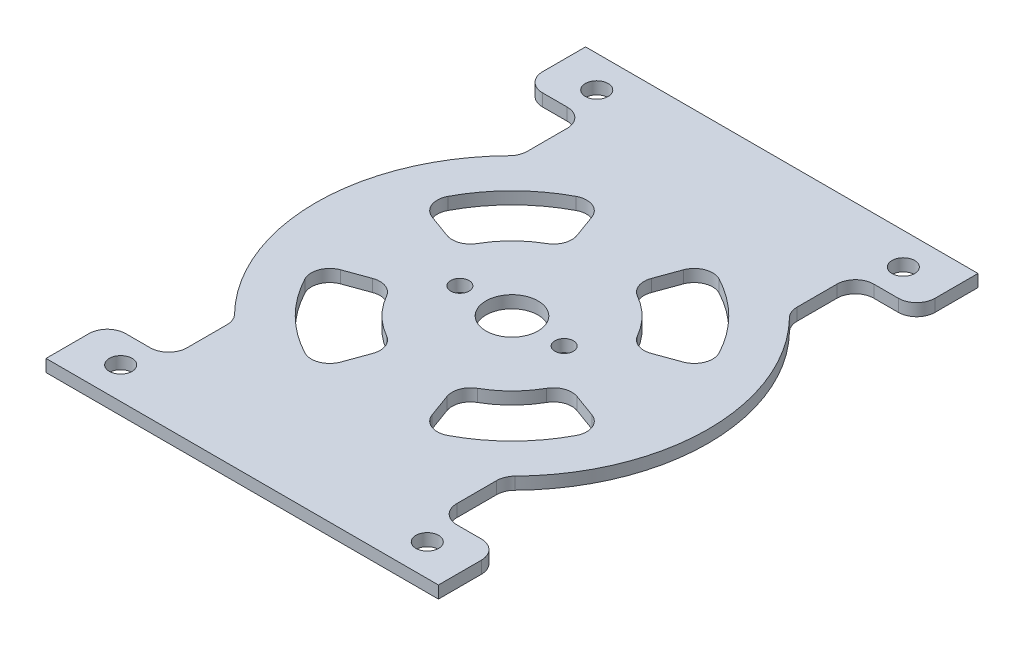
SolidWorks part; units mm, degrees
material "Acrylic (Medium-high impact)"
ref_plane "Front Plane" through (0, 0, 0) normal (0, 0, 1) x (1, 0, 0)
ref_plane "Top Plane" through (0, 0, 0) normal (0, 1, 0) x (1, 0, 0)
ref_plane "Right Plane" through (0, 0, 0) normal (1, 0, 0) x (0, 0, -1)
sketch "Sketch1" plane through (0, 0, 0) normal (0, 1, 0) x (1, 0, 0)
  line L0 (-32, 44) -> (-32, 37)
  line L1 (32, -44) -> (-32, -44)
  line L3 (32, 44) -> (-32, 44)
  line L5 (32, -44) -> (-32, 44) construction
  line L6 (32, 44) -> (-32, -44) construction
  line L7 (-29, 34) -> (-25, 34)
  line L8 (-22, 31) -> (-22, 24.4949)
  line L9 (-32, 34) -> (-32, 44)
  line L10 (32, 44) -> (32, 37)
  line L11 (29, 34) -> (25, 34)
  line L12 (22, 31) -> (22, 24.4949)
  line L13 (-55, 0) -> (55, 0) construction
  line L14 (-22, -31) -> (-22, -24.4949)
  line L15 (-29, -34) -> (-25, -34)
  line L16 (-32, -44) -> (-32, -37)
  line L17 (32, -44) -> (32, -37)
  line L18 (22, -31) -> (22, -24.4949)
  line L19 (29, -34) -> (25, -34)
  circle A0 centre (0, 0) radius 4.25
  arc A1 (-22.8571, 22.3953) -> (-22.8571, -22.3953) centre (0, 0) ccw
  arc A3 (22.8571, -22.3953) -> (22.8571, 22.3953) centre (0, 0) ccw
  arc A4 (-22, 24.4949) -> (-22.8571, 22.3953) centre (-25, 24.4949) cw
  arc A5 (-32, 37) -> (-29, 34) centre (-29, 37) ccw
  arc A6 (-25, 34) -> (-22, 31) centre (-25, 31) cw
  arc A7 (32, 37) -> (29, 34) centre (29, 37) cw
  arc A8 (25, 34) -> (22, 31) centre (25, 31) ccw
  arc A9 (22, 24.4949) -> (22.8571, 22.3953) centre (25, 24.4949) ccw
  arc A10 (32, -37) -> (29, -34) centre (29, -37) ccw
  arc A11 (22, -31) -> (25, -34) centre (25, -31) ccw
  arc A12 (22, -24.4949) -> (22.8571, -22.3953) centre (25, -24.4949) cw
  arc A13 (-22, -24.4949) -> (-22.8571, -22.3953) centre (-25, -24.4949) ccw
  arc A14 (-22, -31) -> (-25, -34) centre (-25, -31) cw
  arc A15 (-29, -34) -> (-32, -37) centre (-29, -37) ccw
  point P0 (0, 0)
  point P25 (-22, 23.2379)
  point P31 (-22, 34)
  point P34 (32, 34)
  point P37 (22, 34)
  point P40 (22, 23.2379)
  point P43 (32, -34)
  point P46 (22, -34)
  point P49 (22, -23.2379)
  point P52 (-22, -23.2379)
  point P55 (-22, -34)
  point P58 (-32, -34)
  dimension "D3" = 8.5
  dimension "D5" = 64
  dimension "D10" = 3
  dimension "D1" = 64
  dimension "D2" = 88
  dimension "D6" = 10
  dimension "D7" = 10
  dimension "D8" = 10
  dimension "D9" = 10
extrude "Boss-Extrude1" add sketch "Sketch1" along normal blind 2 contours L15 A15 L16 L1 L17 A10 L19 A11 L18 A12 A3 A9 L12 A8 L11 A7 L10 L3 L0 A5 L7 A6 L8 A4 A1 A13 L14 A14 A0
sketch "Sketch2" plane through (0, 2, 0) normal (0, 1, 0) x (1, 0, 0)
  line L0 (0, 34.8617) -> (0, -39.3717) construction
  line L1 (-36.4463, 0) -> (53.8771, 0) construction
  line L2 (42.9011, -15.6147) -> (0, 0)
  line L3 (10.8296, -29.754) -> (0, 0)
  line L4 (-6.0703, 16.6779) -> (-7.4542, 20.4801)
  line L5 (-16.6779, 6.0703) -> (-20.4801, 7.4542)
  arc A0 (-11.6741, 22.1069) -> (-22.1069, 11.6741) centre (0, 0) ccw
  arc A1 (-7.4078, 13.0432) -> (-13.0432, 7.4078) centre (0, 0) ccw
  arc A2 (-22.1069, 11.6741) -> (-20.4801, 7.4542) centre (-19.4541, 10.2732) ccw
  arc A3 (-13.0432, 7.4078) -> (-16.6779, 6.0703) centre (-15.6518, 8.8893) cw
  arc A4 (-7.4078, 13.0432) -> (-6.0703, 16.6779) centre (-8.8893, 15.6518) ccw
  arc A5 (-11.6741, 22.1069) -> (-7.4542, 20.4801) centre (-10.2732, 19.4541) cw
  point P11 (0, 0)
  point P12 (-23.4923, 8.5505)
  point P15 (0, 0)
  point P20 (-14.0954, 5.1303)
  point P23 (-5.1303, 14.0954)
  point P26 (-8.5505, 23.4923)
  dimension "D1" = 50
  dimension "D2" = 30
  dimension "D5" = 3
  dimension "D3" = 20
  dimension "D4" = 20
extrude "Cut-Extrude1" cut sketch "Sketch2" against normal blind 5 contours A5 A0 A2 L5 A3 A1 A4 L4
pattern_circular "CirPattern1" count 4 over 360 about axis through (0, 0, 0) along (0, 1, 0) of "Cut-Extrude1"
sketch "Sketch3" plane through (0, 2, 0) normal (0, 1, 0) x (1, 0, 0)
  line L0 (-12.9208, 0) -> (20.4782, 0) construction
  circle A0 centre (-8.5, 0) radius 1.5
  circle A1 centre (8.5, 0) radius 1.5
  dimension "D3" = 3
  dimension "D1" = 8.5
  dimension "D2" = 17
extrude "Cut-Extrude2" cut sketch "Sketch3" against normal blind 5
sketch "Sketch5" plane through (0, 2, 0) normal (0, 1, 0) x (1, 0, 0)
  circle A0 centre (25, 38.82) radius 1.85
  circle A1 centre (-25, 38.82) radius 1.85
  circle A2 centre (-25, -38.82) radius 1.85
  circle A3 centre (25, -38.82) radius 1.85
  dimension "D1" = 3.7
extrude "Cut-Extrude3" cut sketch "Sketch5" against normal blind 5
